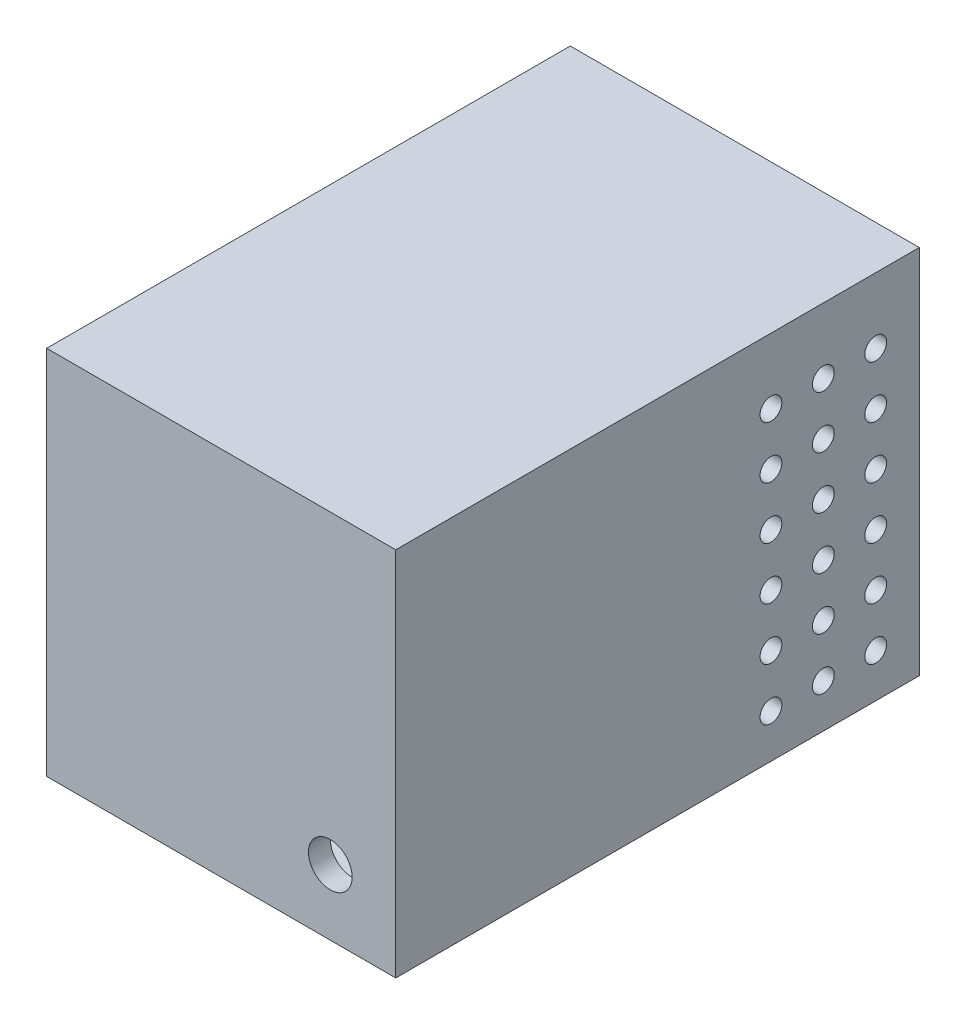
SolidWorks part; units mm, degrees
ref_plane "Front Plane" through (0, 0, 0) normal (0, 0, 1) x (1, 0, 0)
ref_plane "Top Plane" through (0, 0, 0) normal (0, 1, 0) x (1, 0, 0)
ref_plane "Right Plane" through (0, 0, 0) normal (1, 0, 0) x (0, 0, -1)
sketch "Sketch1" plane through (0, 0, 0) normal (0, 1, 0) x (1, 0, 0)
  line L1 (0, 0) -> (101.6, 0)
  line L2 (0, 0) -> (0, 152.4)
  line L3 (0, 152.4) -> (101.6, 152.4)
  line L4 (101.6, 0) -> (101.6, 152.4)
  line L5 (0, 0) -> (101.6, 152.4) construction
  line L6 (0, 152.4) -> (101.6, 0) construction
  point P4 (50.8, 76.2)
  dimension "D1" = 152.4
  dimension "D2" = 101.6
extrude "Boss-Extrude1" add sketch "Sketch1" along normal blind 101.6
sketch "Sketch3" plane through (0, 101.6, 0) normal (0, 1, 0) x (1, 0, 0)
  line L0 (0, 152.4) -> (0, 0) construction
  line L1 (6.35, 146.05) -> (95.25, 146.05)
  line L2 (6.35, 146.05) -> (6.35, 6.35)
  line L3 (6.35, 6.35) -> (95.25, 6.35)
  line L4 (95.25, 146.05) -> (95.25, 6.35)
  line L5 (6.35, 146.05) -> (95.25, 6.35) construction
  line L6 (6.35, 6.35) -> (95.25, 146.05) construction
  line L7 (101.6, 152.4) -> (0, 152.4) construction
  line L8 (101.6, 0) -> (101.6, 152.4) construction
  line L9 (0, 0) -> (101.6, 0) construction
  point P4 (50.8, 76.2)
  dimension "D1" = 6.35
  dimension "D2" = 6.35
  dimension "D3" = 6.35
  dimension "D4" = 6.35
extrude "Cut-Extrude1" cut sketch "Sketch3" against normal blind 95.25
sketch "Sketch4" plane through (0, 6.35, 0) normal (0, 1, 0) x (1, 0, 0)
  line L1 (6.35, 101.6) -> (95.25, 101.6)
  line L2 (6.35, 101.6) -> (6.35, 95.25)
  line L3 (6.35, 95.25) -> (95.25, 95.25)
  line L4 (95.25, 101.6) -> (95.25, 95.25)
  line L5 (6.35, 101.6) -> (95.25, 95.25) construction
  line L6 (6.35, 95.25) -> (95.25, 101.6) construction
  line L7 (6.35, 146.05) -> (6.35, 6.35) construction
  line L9 (95.25, 6.35) -> (95.25, 146.05) construction
  line L11 (95.25, 146.05) -> (6.35, 146.05) construction
  point P4 (50.8, 98.425)
  dimension "D1" = 6.35
  dimension "D2" = 44.45
extrude "Boss-Extrude2" add sketch "Sketch4" along normal blind 95.25
sketch "Sketch6" plane through (95.25, 0, 0) normal (-1, 0, 0) x (0, 0, 1)
  line L0 (-146.05, 6.35) -> (-146.05, 101.6) construction
  line L1 (-101.6, 6.35) -> (-146.05, 6.35) construction
  line L2 (-139.7, 12.7) -> (-124.46, 12.7) construction
  circle A0 centre (-139.7, 12.7) radius 3.175
  circle A1 centre (-124.46, 12.7) radius 3.175
  circle A2 centre (-109.22, 12.7) radius 3.175
  circle A3 centre (-124.46, 27.94) radius 3.175
  circle A4 centre (-109.22, 27.94) radius 3.175
  circle A5 centre (-124.46, 43.18) radius 3.175
  circle A6 centre (-109.22, 43.18) radius 3.175
  circle A7 centre (-124.46, 58.42) radius 3.175
  circle A8 centre (-109.22, 58.42) radius 3.175
  circle A9 centre (-124.46, 73.66) radius 3.175
  circle A10 centre (-109.22, 73.66) radius 3.175
  circle A11 centre (-124.46, 88.9) radius 3.175
  circle A12 centre (-109.22, 88.9) radius 3.175
  circle A13 centre (-139.7, 27.94) radius 3.175
  circle A14 centre (-139.7, 43.18) radius 3.175
  circle A15 centre (-139.7, 58.42) radius 3.175
  circle A16 centre (-139.7, 73.66) radius 3.175
  circle A17 centre (-139.7, 88.9) radius 3.175
  dimension "D1" = 6.35
  dimension "D2" = 6.35
  dimension "D5" = 15.24
  dimension "D3" = 3
  dimension "D4" = 6
extrude "Cut-Extrude2" cut sketch "Sketch6" against normal through all
sketch "Sketch7" plane through (6.35, 0, 0) normal (1, 0, 0) x (0, 0, -1)
  line L0 (146.05, 6.35) -> (101.6, 6.35) construction
  line L1 (146.05, 6.35) -> (146.05, 101.6) construction
  line L2 (139.7, 12.7) -> (124.46, 12.7) construction
  circle A0 centre (139.7, 12.7) radius 3.175
  circle A1 centre (124.46, 12.7) radius 3.175
  circle A2 centre (109.22, 12.7) radius 3.175
  circle A3 centre (124.46, 27.94) radius 3.175
  circle A4 centre (109.22, 27.94) radius 3.175
  circle A5 centre (124.46, 43.18) radius 3.175
  circle A6 centre (109.22, 43.18) radius 3.175
  circle A7 centre (124.46, 58.42) radius 3.175
  circle A8 centre (109.22, 58.42) radius 3.175
  circle A9 centre (124.46, 73.66) radius 3.175
  circle A10 centre (109.22, 73.66) radius 3.175
  circle A11 centre (124.46, 88.9) radius 3.175
  circle A12 centre (109.22, 88.9) radius 3.175
  circle A13 centre (139.7, 27.94) radius 3.175
  circle A14 centre (139.7, 43.18) radius 3.175
  circle A15 centre (139.7, 58.42) radius 3.175
  circle A16 centre (139.7, 73.66) radius 3.175
  circle A17 centre (139.7, 88.9) radius 3.175
  dimension "D1" = 6.35
  dimension "D2" = 6.35
  dimension "D5" = 15.24
  dimension "D3" = 3
  dimension "D4" = 6
extrude "Cut-Extrude3" cut sketch "Sketch7" against normal through all
sketch "Sketch8" plane through (0, 0, -152.4) normal (0, 0, -1) x (-1, 0, 0)
  line L0 (-101.6, 0) -> (0, 0) construction
  line L1 (-101.6, 101.6) -> (-101.6, 0) construction
  line L2 (-88.9, 12.7) -> (-73.66, 12.7) construction
  circle A0 centre (-88.9, 12.7) radius 3.175
  circle A1 centre (-73.66, 12.7) radius 3.175
  circle A2 centre (-58.42, 12.7) radius 3.175
  circle A3 centre (-43.18, 12.7) radius 3.175
  circle A4 centre (-27.94, 12.7) radius 3.175
  circle A5 centre (-12.7, 12.7) radius 3.175
  circle A6 centre (-73.66, 27.94) radius 3.175
  circle A7 centre (-58.42, 27.94) radius 3.175
  circle A8 centre (-43.18, 27.94) radius 3.175
  circle A9 centre (-27.94, 27.94) radius 3.175
  circle A10 centre (-12.7, 27.94) radius 3.175
  circle A11 centre (-73.66, 43.18) radius 3.175
  circle A12 centre (-58.42, 43.18) radius 3.175
  circle A13 centre (-43.18, 43.18) radius 3.175
  circle A14 centre (-27.94, 43.18) radius 3.175
  circle A15 centre (-12.7, 43.18) radius 3.175
  circle A16 centre (-73.66, 58.42) radius 3.175
  circle A17 centre (-58.42, 58.42) radius 3.175
  circle A18 centre (-43.18, 58.42) radius 3.175
  circle A19 centre (-27.94, 58.42) radius 3.175
  circle A20 centre (-12.7, 58.42) radius 3.175
  circle A21 centre (-73.66, 73.66) radius 3.175
  circle A22 centre (-58.42, 73.66) radius 3.175
  circle A23 centre (-43.18, 73.66) radius 3.175
  circle A24 centre (-27.94, 73.66) radius 3.175
  circle A25 centre (-12.7, 73.66) radius 3.175
  circle A26 centre (-73.66, 88.9) radius 3.175
  circle A27 centre (-58.42, 88.9) radius 3.175
  circle A28 centre (-43.18, 88.9) radius 3.175
  circle A29 centre (-27.94, 88.9) radius 3.175
  circle A30 centre (-12.7, 88.9) radius 3.175
  circle A31 centre (-88.9, 27.94) radius 3.175
  circle A32 centre (-88.9, 43.18) radius 3.175
  circle A33 centre (-88.9, 58.42) radius 3.175
  circle A34 centre (-88.9, 73.66) radius 3.175
  circle A35 centre (-88.9, 88.9) radius 3.175
  dimension "D1" = 12.7
  dimension "D2" = 12.7
  dimension "D5" = 15.24
  dimension "D3" = 6
  dimension "D4" = 6
extrude "Cut-Extrude5" cut sketch "Sketch8" against normal up to next (6.35 mm away) and the other way through all
sketch "Sketch9" plane through (0, 101.6, 0) normal (0, 1, 0) x (1, 0, 0)
  line L1 (0, 152.4) -> (101.6, 152.4)
  line L2 (0, 152.4) -> (0, 0)
  line L3 (0, 0) -> (101.6, 0)
  line L4 (101.6, 152.4) -> (101.6, 0)
  line L5 (0, 152.4) -> (101.6, 0) construction
  line L6 (0, 0) -> (101.6, 152.4) construction
  point P4 (50.8, 76.2)
extrude "Boss-Extrude3" add sketch "Sketch9" along normal blind 6.35
sketch "Sketch10" plane through (0, 0, -6.35) normal (0, 0, -1) x (-1, 0, 0)
  line L0 (-95.25, 6.35) -> (-95.25, 101.6) construction
  line L1 (-6.35, 6.35) -> (-95.25, 6.35) construction
  circle A0 centre (-82.55, 19.05) radius 6.35
  dimension "D1" = 12.7
  dimension "D2" = 12.7
extrude "Cut-Extrude6" cut sketch "Sketch10" against normal blind 6.35
